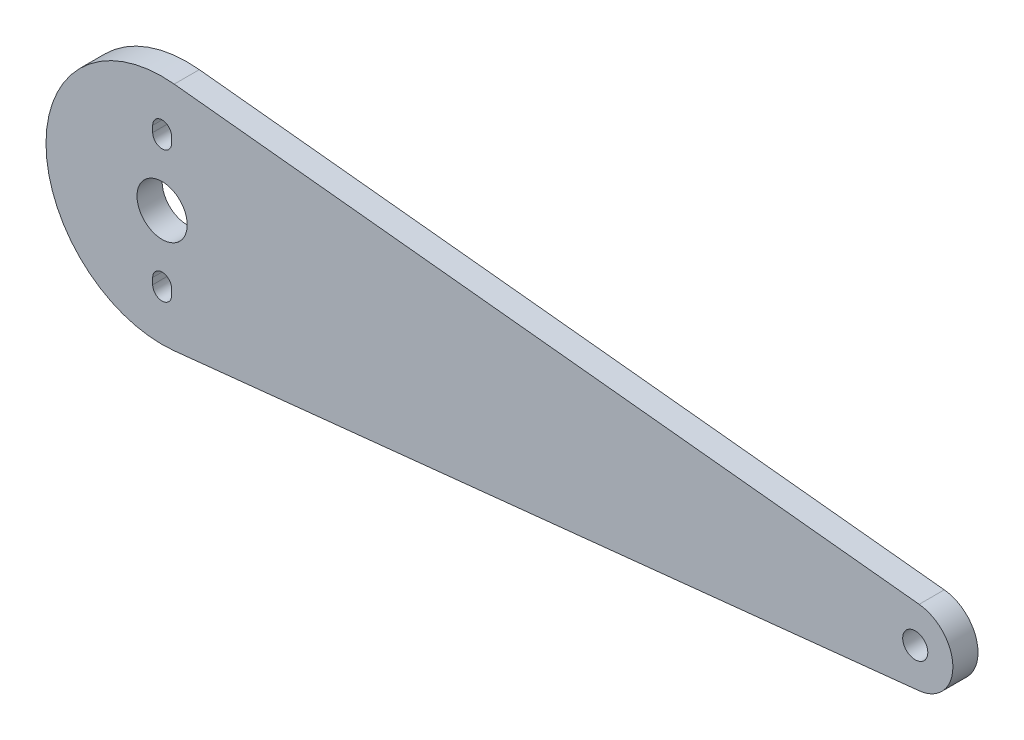
SolidWorks part; units mm, degrees
ref_plane "Front Plane" through (0, 0, 0) normal (0, 0, 1) x (1, 0, 0)
ref_plane "Top Plane" through (0, 0, 0) normal (0, 1, 0) x (1, 0, 0)
ref_plane "Right Plane" through (0, 0, 0) normal (1, 0, 0) x (0, 0, -1)
sketch "Sketch1" plane through (0, 0, 0) normal (0, 0, 1) x (1, 0, 0)
  line L0 (-60, 0) -> (60, 0) construction
  line L1 (-58.0729, 18.3994) -> (60.625, 5.9674)
  line L2 (-58.0729, -18.3994) -> (60.625, -5.9674)
  line L3 (-60, 11) -> (-60, 10) construction
  line L4 (-58.5, 11) -> (-58.5, 10)
  line L5 (-61.5, 11) -> (-61.5, 10)
  line L6 (-60, -11) -> (-60, -10) construction
  line L7 (-58.5, -11) -> (-58.5, -10)
  line L8 (-61.5, -11) -> (-61.5, -10)
  arc A0 (-58.0729, 18.3994) -> (-58.0729, -18.3994) centre (-60, 0) ccw
  arc A1 (60.625, -5.9674) -> (60.625, 5.9674) centre (60, 0) ccw
  circle A2 centre (60, 0) radius 2
  circle A3 centre (-60, 0) radius 4
  arc A4 (-58.5, -11) -> (-61.5, -11) centre (-60, -11) cw
  arc A5 (-58.5, 11) -> (-61.5, 11) centre (-60, 11) ccw
  arc A6 (-61.5, 10) -> (-58.5, 10) centre (-60, 10) ccw
  arc A7 (-61.5, -10) -> (-58.5, -10) centre (-60, -10) cw
  point P13 (-60, 10.5)
  point P18 (-60, -10.5)
  dimension "D1" = 37
  dimension "D2" = 12
  dimension "D4" = 8
  dimension "D5" = 4
  dimension "D6" = 10.5
  dimension "D7" = 1.5
  dimension "D3" = 120
  dimension "D8" = 1
extrude "Boss-Extrude1" add sketch "Sketch1" along normal blind 4
